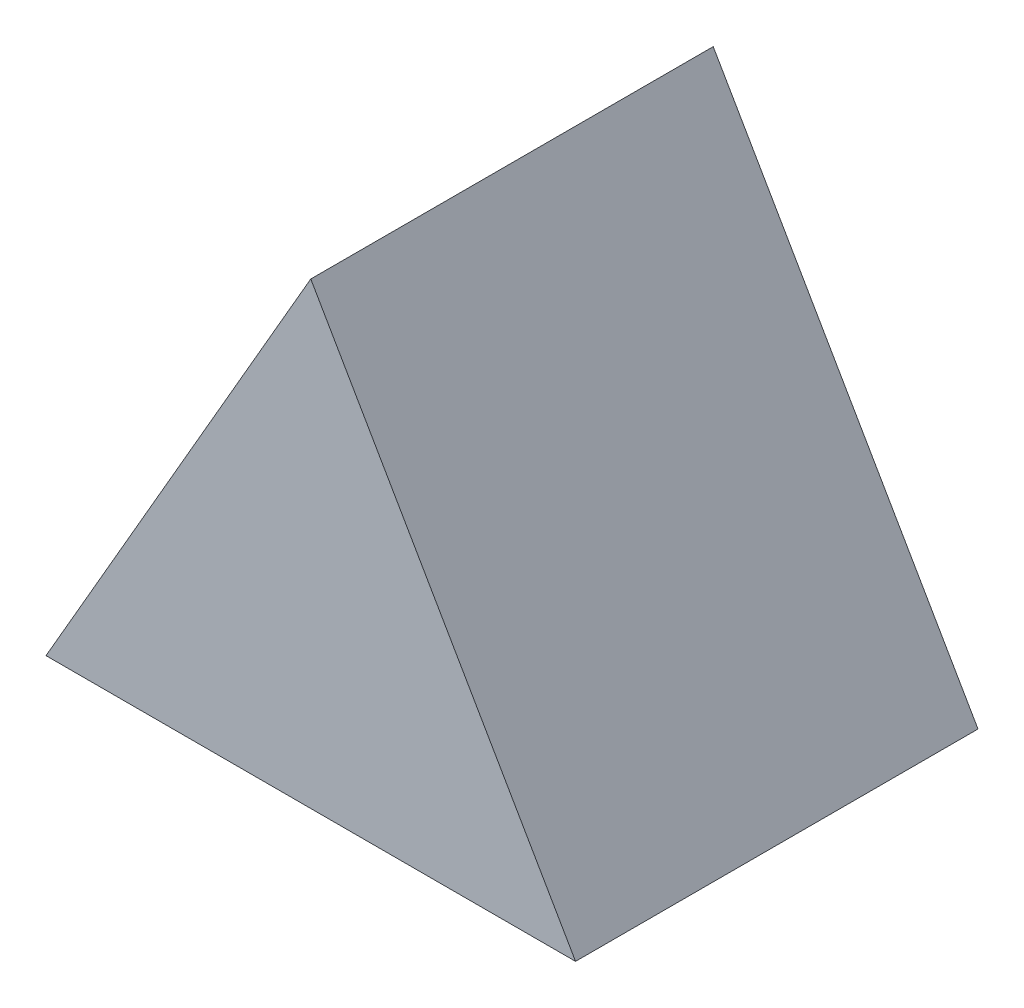
SolidWorks part; units mm, degrees
ref_plane "Спереди" through (0, 0, 0) normal (0, 0, 1) x (1, 0, 0)
ref_plane "Сверху" through (0, 0, 0) normal (0, 1, 0) x (1, 0, 0)
ref_plane "Справа" through (0, 0, 0) normal (1, 0, 0) x (0, 0, -1)
other "Configuration Table"
sketch "Эскиз1" plane through (0, 0, 0) normal (0, 0, 1) x (1, 0, 0)
  line L0 (-2.8464, -2.4651) -> (2.8464, -2.4651)
  line L1 (2.8464, -2.4651) -> (0, 2.4651)
  line L2 (0, 2.4651) -> (-2.8464, -2.4651)
sketch "Эскиз2" plane through (0, 0, 0) normal (0, 0, 1) x (1, 0, 0)
  line L0 (-2.5, -2.2651) -> (0, 2.0651)
  line L1 (0, 2.0651) -> (2.5, -2.2651)
  line L2 (2.5, -2.2651) -> (-2.5, -2.2651)
  line L3 (-2.8464, -2.4651) -> (2.8464, -2.4651) construction
  line L4 (2.8464, -2.4651) -> (0, 2.4651) construction
  line L5 (0, 2.4651) -> (-2.8464, -2.4651) construction
  dimension "D1" = 0.2
  dimension "D2" = 0.2
  dimension "D3" = 0.2
extrude "Бобышка-Вытянуть1" add sketch "Эскиз2" along normal blind 3.8
